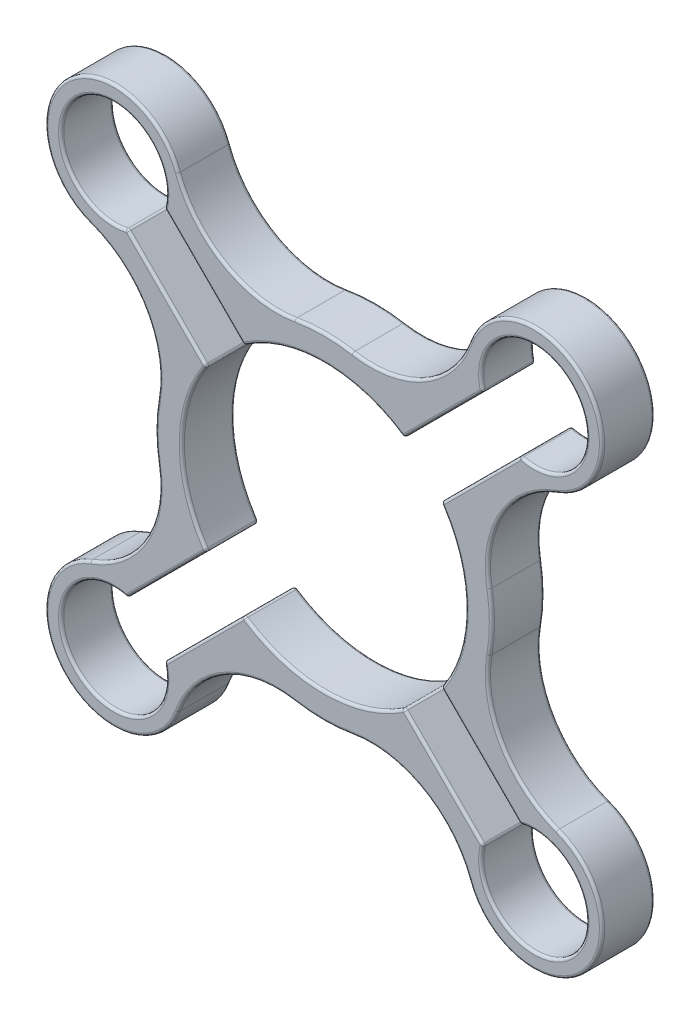
SolidWorks part; units mm, degrees
material "Cast Carbon Steel"
ref_plane "Front Plane" through (0, 0, 0) normal (0, 0, 1) x (1, 0, 0)
ref_plane "Top Plane" through (0, 0, 0) normal (0, 1, 0) x (1, 0, 0)
ref_plane "Right Plane" through (0, 0, 0) normal (1, 0, 0) x (0, 0, -1)
sketch "Sketch1" plane through (0, 0, 0) normal (0, 0, 1) x (1, 0, 0)
  line L0 (0, 0) -> (50000, 0) construction
  line L1 (0, 0) -> (35355.3391, 35355.3391) construction
  line L2 (33.7288, 26.6577) -> (25.885, 18.814)
  line L3 (26.6577, 33.7288) -> (18.814, 25.885)
  line L4 (26.6577, 33.7288) -> (30.2923, 37.3633)
  line L5 (33.7288, 26.6577) -> (37.3633, 30.2923)
  line L6 (18.814, 25.885) -> (15.2261, 22.2972)
  line L7 (25.885, 18.814) -> (22.2972, 15.2261)
  line L8 (26.6577, -33.7288) -> (18.814, -25.885)
  line L9 (33.7288, -26.6577) -> (25.885, -18.814)
  line L10 (33.7288, -26.6577) -> (37.3633, -30.2923)
  line L11 (26.6577, -33.7288) -> (30.2923, -37.3633)
  line L12 (25.885, -18.814) -> (22.2972, -15.2261)
  line L13 (18.814, -25.885) -> (15.2261, -22.2972)
  line L14 (-33.7288, -26.6577) -> (-25.885, -18.814)
  line L15 (-26.6577, -33.7288) -> (-18.814, -25.885)
  line L16 (-26.6577, -33.7288) -> (-30.2923, -37.3633)
  line L17 (-33.7288, -26.6577) -> (-37.3633, -30.2923)
  line L18 (-18.814, -25.885) -> (-15.2261, -22.2972)
  line L19 (-25.885, -18.814) -> (-22.2972, -15.2261)
  line L20 (-26.6577, 33.7288) -> (-18.814, 25.885)
  line L21 (-33.7288, 26.6577) -> (-25.885, 18.814)
  line L22 (-33.7288, 26.6577) -> (-37.3633, 30.2923)
  line L23 (-26.6577, 33.7288) -> (-30.2923, 37.3633)
  line L24 (-25.885, 18.814) -> (-22.2972, 15.2261)
  line L25 (-18.814, 25.885) -> (-15.2261, 22.2972)
  arc A0 (5.4999, 31.5238) -> (-5.4999, 31.5238) centre (0, 0) ccw
  arc A1 (15.2261, 22.2972) -> (-15.2261, 22.2972) centre (0, 0) ccw
  arc A2 (37.3633, 30.2923) -> (30.2923, 37.3633) centre (39.9515, 39.9515) ccw
  arc A3 (44.3931, 27.7338) -> (27.7338, 44.3931) centre (39.9515, 39.9515) ccw
  circle A4 centre (0, 0) radius 56.5 construction
  arc A5 (27.7338, 44.3931) -> (5.4999, 31.5238) centre (8.9373, 51.2262) cw
  arc A6 (44.3931, 27.7338) -> (31.5238, 5.4999) centre (51.2262, 8.9373) ccw
  arc A7 (30.2923, -37.3633) -> (37.3633, -30.2923) centre (39.9515, -39.9515) ccw
  arc A8 (27.7338, -44.3931) -> (44.3931, -27.7338) centre (39.9515, -39.9515) ccw
  arc A9 (44.3931, -27.7338) -> (31.5238, -5.4999) centre (51.2262, -8.9373) cw
  arc A10 (27.7338, -44.3931) -> (5.4999, -31.5238) centre (8.9373, -51.2262) ccw
  arc A11 (-37.3633, -30.2923) -> (-30.2923, -37.3633) centre (-39.9515, -39.9515) ccw
  arc A12 (-44.3931, -27.7338) -> (-27.7338, -44.3931) centre (-39.9515, -39.9515) ccw
  arc A13 (-27.7338, -44.3931) -> (-5.4999, -31.5238) centre (-8.9373, -51.2262) cw
  arc A14 (-44.3931, -27.7338) -> (-31.5238, -5.4999) centre (-51.2262, -8.9373) ccw
  arc A15 (-30.2923, 37.3633) -> (-37.3633, 30.2923) centre (-39.9515, 39.9515) ccw
  arc A16 (-27.7338, 44.3931) -> (-44.3931, 27.7338) centre (-39.9515, 39.9515) ccw
  arc A17 (-44.3931, 27.7338) -> (-31.5238, 5.4999) centre (-51.2262, 8.9373) cw
  arc A18 (-27.7338, 44.3931) -> (-5.4999, 31.5238) centre (-8.9373, 51.2262) ccw
  arc A19 (-31.5238, 5.4999) -> (-31.5238, -5.4999) centre (0, 0) ccw
  arc A20 (-22.2972, 15.2261) -> (-22.2972, -15.2261) centre (0, 0) ccw
  arc A21 (-15.2261, -22.2972) -> (15.2261, -22.2972) centre (0, 0) ccw
  arc A22 (-5.4999, -31.5238) -> (5.4999, -31.5238) centre (0, 0) ccw
  arc A23 (22.2972, -15.2261) -> (22.2972, 15.2261) centre (0, 0) ccw
  arc A24 (31.5238, -5.4999) -> (31.5238, 5.4999) centre (0, 0) ccw
  point P7 (0, 0)
  point P9 (0, 0)
  point P17 (29.8069, 22.7358)
  point P70 (0, 0)
  point P71 (0, 0)
  point P72 (-34.13, 27.0589)
  point P73 (-33.7288, 26.6577)
  dimension "D2" = 64
  dimension "D3" = 54
  dimension "D4" = 20
  dimension "D5" = 26
  dimension "D7" = 113
  dimension "D8" = 20
  dimension "D1" = 45
  dimension "D6" = 10
  dimension "D9" = 4
extrude "Boss-Extrude1" add sketch "Sketch1" along normal mid plane 10
fillet "Fillet1" radius 0.5 80 edges at (49.1439, 49.1439, 5) (33.9167, 18.9563, 5) (32, 0, 5) (33.9167, -18.9563, 5) (49.1439, -49.1439, 5) (18.9563, -33.9167, 5) (0, -32, 5) (-18.9563, -33.9167, 5) (-49.1439, -49.1439, 5) (-33.9167, -18.9563, 5) (-32, 0, 5) (-33.9167, 18.9563, 5) (-49.1439, 49.1439, 5) (-18.9563, 33.9167, 5) (0, 32, 5) (18.9563, 33.9167, 5) (49.1439, 49.1439, -5) (33.9167, 18.9563, -5) (32, 0, -5) (33.9167, -18.9563, -5) (49.1439, -49.1439, -5) (18.9563, -33.9167, -5) (0, -32, -5) (-18.9563, -33.9167, -5) (-49.1439, -49.1439, -5) (-33.9167, -18.9563, -5) (-32, 0, -5) (-33.9167, 18.9563, -5) (-49.1439, 49.1439, -5) (-18.9563, 33.9167, -5) (0, 32, -5) (18.9563, 33.9167, -5) (-15.2261, 22.2972, 0) (-30.2923, 37.3633, 0) (-37.3633, 30.2923, 0) (-22.2972, 15.2261, 0) (-22.2972, -15.2261, 0) (-37.3633, -30.2923, 0) (-30.2923, -37.3633, 0) (-15.2261, -22.2972, 0) (15.2261, -22.2972, 0) (30.2923, -37.3633, 0) (37.3633, -30.2923, 0) (22.2972, -15.2261, 0) (22.2972, 15.2261, 0) (37.3633, 30.2923, 0) (30.2923, 37.3633, 0) (15.2261, 22.2972, 0) (22.7592, 29.8303, 5) (47.0226, 47.0226, 5) (29.8303, 22.7592, 5) (27, 0, 5) (29.8303, -22.7592, 5) (47.0226, -47.0226, 5) (22.7592, -29.8303, 5) (0, -27, 5) (-22.7592, -29.8303, 5) (-47.0226, -47.0226, 5) (-29.8303, -22.7592, 5) (-27, 0, 5) (-29.8303, 22.7592, 5) (-47.0226, 47.0226, 5) (-22.7592, 29.8303, 5) (0, 27, 5) (22.7592, 29.8303, -5) (47.0226, 47.0226, -5) (29.8303, 22.7592, -5) (27, 0, -5) (29.8303, -22.7592, -5) (47.0226, -47.0226, -5) (22.7592, -29.8303, -5) (0, -27, -5) (-22.7592, -29.8303, -5) (-47.0226, -47.0226, -5) (-29.8303, -22.7592, -5) (-27, 0, -5) (-29.8303, 22.7592, -5) (-47.0226, 47.0226, -5) (-22.7592, 29.8303, -5) (0, 27, -5)
